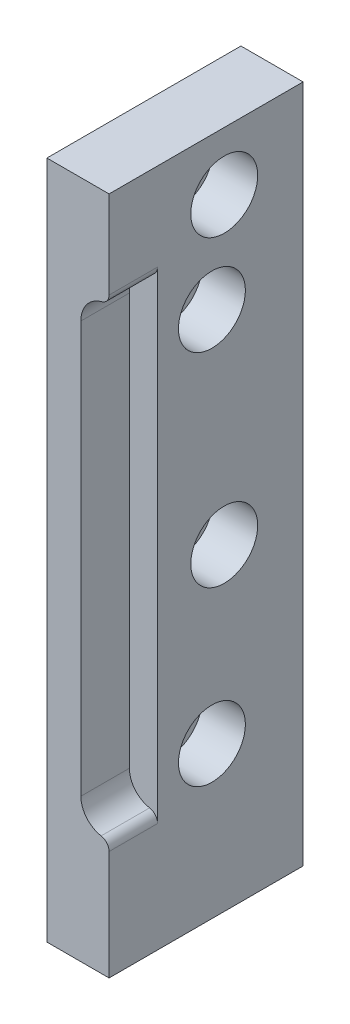
SolidWorks part; units mm, degrees
material "6061-T6 (SS)"
ref_plane "X-Y Datum" through (0, 0, 0) normal (0, 0, 1) x (1, 0, 0)
ref_plane "X-Z Datum" through (0, 0, 0) normal (0, 1, 0) x (1, 0, 0)
ref_plane "Y-Z Datum" through (0, 0, 0) normal (1, 0, 0) x (0, 0, -1)
sketch "Sketch1" plane through (0, 0, 0) normal (0, 0, 1) x (1, 0, 0)
  line L1 (8.1407, 88.9) -> (-8.1407, 88.9)
  line L6 (-8.1407, 88.9) -> (-8.1407, -88.9)
  line L7 (-8.1407, -88.9) -> (8.1407, -88.9)
  line L9 (8.1407, 88.9) -> (8.1407, -88.9)
  point P0 (8.1407, 0)
  point P2 (0, 88.9)
  dimension "D4" = 177.8
  dimension "D6" = 16.2814
extrude "Boss-Extrude1" add sketch "Sketch1" along normal mid plane 50.8
sketch "Sketch2" plane through (8.1407, 0, 0) normal (1, 0, 0) x (0, 0, -1)
  line L0 (1.524, 49.2117) -> (1.524, -49.2117) construction
  line L1 (25.4, -88.9) -> (25.4, 88.9) construction
  circle A0 centre (1.524, 49.2117) radius 6.7577
  circle A1 centre (1.524, -49.2117) radius 6.7577
  point P4 (1.524, 49.2117)
  point P5 (1.524, -49.2117)
  point P6 (25.4, 0)
  point P10 (1.524, 0)
  dimension "D2" = 13.5153
  dimension "D1" = 98.4235
  dimension "D3" = 23.876
extrude "Cut-Extrude1" cut sketch "Sketch2" against normal through all
sketch "Sketch3" plane through (8.1407, 0, 0) normal (1, 0, 0) x (0, 0, -1)
  circle A0 centre (1.524, 49.2117) radius 8.7641
  circle A1 centre (1.524, -49.2117) radius 8.7641
  dimension "D1" = 17.5282
extrude "Cut-Extrude2" cut sketch "Sketch3" against normal offset from surface (11.3284 mm away) 4.953 up to face at (-8.1407, 49.2117, -8.2817)
sketch "Sketch4" plane through (0, 0, 25.4) normal (0, 0, 1) x (1, 0, 0)
  line L0 (0.7493, -51.3817) -> (0.7493, 56.3806)
  line L1 (0.7493, -51.3817) -> (0.7493, 56.3806) construction
  line L2 (8.1407, 63.7556) -> (8.1407, -57.7498)
  line L3 (8.1407, -88.9) -> (8.1407, 88.9) construction
  arc A0 (0.7493, -51.3817) -> (9.9437, -57.2012) centre (7.1882, -51.3817) ccw construction
  arc A1 (15.1476, 58.6308) -> (0.7493, 56.3806) centre (8.1243, 56.3806) ccw construction
  arc A2 (0.7493, -51.3817) -> (8.1407, -57.7498) centre (7.1882, -51.3817) ccw
  arc A3 (8.1407, 63.7556) -> (0.7493, 56.3806) centre (8.1243, 56.3806) ccw
extrude "Cut-Extrude3" cut sketch "Sketch4" against normal blind 12.7
sketch "Sketch5" plane through (8.1407, 0, 0) normal (1, 0, 0) x (0, 0, -1)
  line L0 (25.4, -88.9) -> (25.4, 88.9) construction
  line L1 (-25.4, 88.9) -> (25.4, 88.9) construction
  circle A0 centre (4.7498, -5.715) radius 5.715
  circle A1 centre (4.7498, 73.66) radius 5.715
  point P4 (4.7498, -6.4162)
  point P5 (2.9873, 67.899)
  point P6 (0, 72.8036)
  point P8 (2.7538, 73.7378)
  point P9 (3.688, 71.8694)
  point P10 (0, 73.5933)
  point P13 (4.7498, 69.8962)
  point P14 (4.7498, 70.9977)
  point P15 (4.7498, 69.8932)
  dimension "D1" = 11.43
  dimension "D2" = 11.43
  dimension "D4" = 15.24
  dimension "D3" = 79.375
  dimension "D6" = 20.6502
extrude "Cut-Extrude4" cut sketch "Sketch5" against normal through all
sketch "Sketch6" plane through (8.1407, 0, 0) normal (1, 0, 0) x (0, 0, -1)
  circle A0 centre (4.7498, -5.715) radius 8.763
  circle A1 centre (4.7498, 73.66) radius 8.763
  dimension "D1" = 17.526
  dimension "D2" = 17.526
extrude "Cut-Extrude5" cut sketch "Sketch6" against normal offset from surface (11.684 mm away) 4.5974 up to face at (-8.1407, -5.715, -10.4648)
fillet "Fillet1" radius 2.54 2 edges at (8.1407, 63.7556, 19.05) (8.1407, -57.7498, 19.05)
